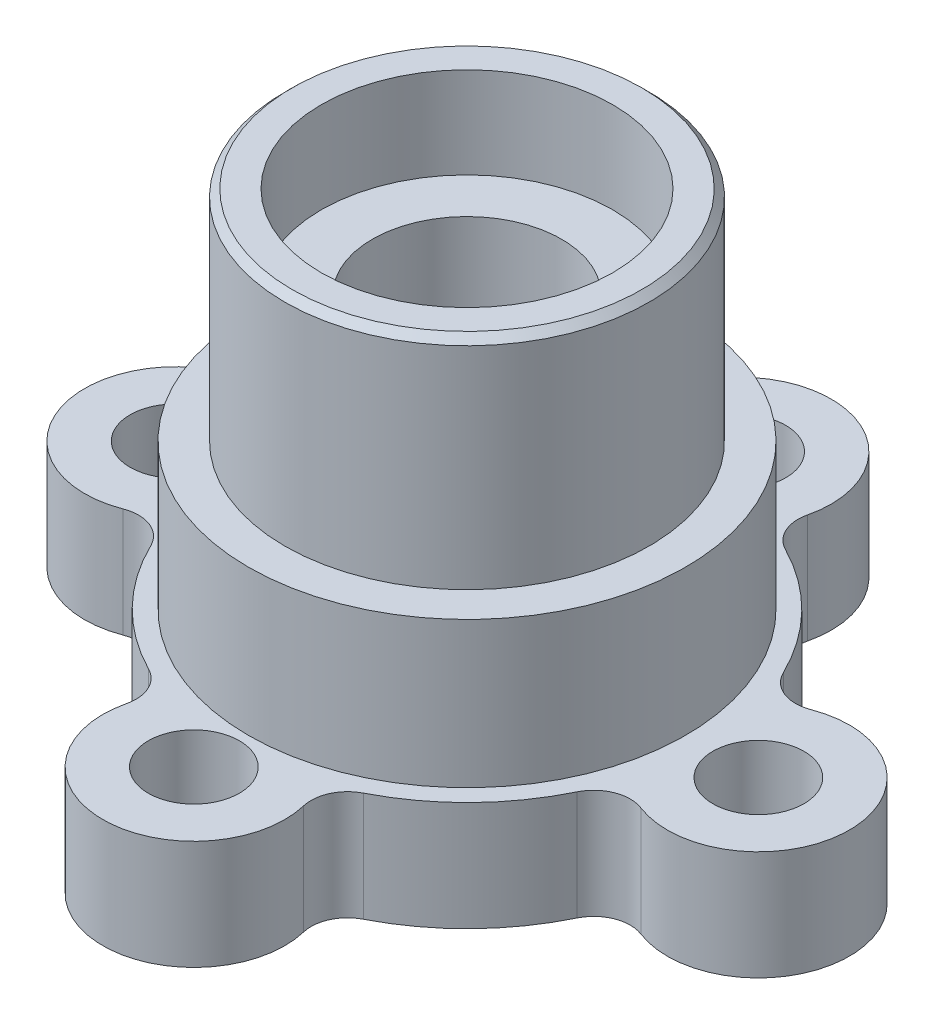
SolidWorks part; units mm, degrees
material "1060 Alloy"
ref_plane "Front Plane" through (0, 0, 0) normal (0, 0, 1) x (1, 0, 0)
ref_plane "Top Plane" through (0, 0, 0) normal (0, 1, 0) x (1, 0, 0)
ref_plane "Right Plane" through (0, 0, 0) normal (1, 0, 0) x (0, 0, -1)
sketch "Sketch1" plane through (0, 0, 0) normal (0, 1, 0) x (1, 0, 0)
  line L0 (0, 0) -> (0, 7.9047) construction
  line L1 (0, 0) -> (8, 0) construction
  arc A0 (-2.1042, 6.15) -> (-6.25, 1.7854) centre (0, 0) ccw
  arc A1 (2.1042, 6.15) -> (-2.1042, 6.15) centre (0, 7.5) ccw
  arc A2 (6.25, -1.7854) -> (6.25, 1.7854) centre (8, 0) ccw
  arc A3 (-2.1042, -6.15) -> (2.1042, -6.15) centre (0, -7.5) ccw
  arc A4 (-6.25, 1.7854) -> (-6.25, -1.7854) centre (-8, 0) ccw
  arc A5 (6.25, 1.7854) -> (2.1042, 6.15) centre (0, 0) ccw
  arc A6 (2.1042, -6.15) -> (6.25, -1.7854) centre (0, 0) ccw
  arc A7 (-6.25, -1.7854) -> (-2.1042, -6.15) centre (0, 0) ccw
  dimension "D1" = 16
  dimension "D2" = 15
  dimension "D3" = 13
  dimension "D4" = 5
extrude "Boss-Extrude1" add sketch "Sketch1" along normal blind 3
sketch "Sketch2" plane through (0, 3, 0) normal (0, 1, 0) x (1, 0, 0)
  circle A0 centre (0, 0) radius 6
  dimension "D1" = 12
extrude "Boss-Extrude2" add sketch "Sketch2" along normal blind 4
sketch "Sketch3" plane through (0, 7, 0) normal (0, 1, 0) x (1, 0, 0)
  circle A0 centre (0, 0) radius 5
  dimension "D1" = 10
extrude "Boss-Extrude3" add sketch "Sketch3" along normal blind 6
sketch "Sketch4" plane through (0, 13, 0) normal (0, 1, 0) x (1, 0, 0)
  circle A0 centre (0, 0) radius 2.6
  dimension "D1" = 5.2
extrude "Cut-Extrude1" cut sketch "Sketch4" against normal through all
sketch "Sketch5" plane through (0, 13, 0) normal (0, 1, 0) x (1, 0, 0)
  circle A0 centre (0, 0) radius 4
  dimension "D1" = 8
extrude "Cut-Extrude2" cut sketch "Sketch5" against normal blind 2.5
sketch "Sketch6" plane through (0, 0, 0) normal (0, -1, 0) x (1, 0, 0)
  circle A0 centre (0, 0) radius 4
  dimension "D1" = 8
extrude "Cut-Extrude3" cut sketch "Sketch6" against normal blind 3
hole_wizard "M3x0.5 Tapped Hole1" positions "Sketch7" profile "Sketch8" tap size "M3x0.5" standard "JIS" end condition through all
sketch "Sketch7" plane through (0, 3, 0) normal (0, 1, 0) x (1, 0, 0)
  point P0 (0, 7.5)
  point P2 (8, 0)
  point P5 (0, -7.5)
  point P7 (-8, 0)
  point P17 (0, 0)
  point P18 (0.1338, 7.2678)
  point P19 (0, 0)
  point P20 (0, 7.4758)
  point P21 (4.6603, -7.8537)
  point P22 (0, -7.5)
  point P24 (4.6335, 7.5)
  point P25 (0, 7.5)
sketch "Sketch8" plane through (0, 3, -7.5) normal (1, 0, 0) x (0, 0, 1)
  line L0 (0, 0) -> (0, 3)
  line L1 (0, 3) -> (1.25, 3)
  line L2 (1.25, 3) -> (1.25, 0)
  line L5 (1.25, 0) -> (0, 0)
  line L11 (0, -6.35) -> (0, 107.95) construction
  dimension "Thru Tap Drill Dia." = 2.5
  dimension "Thru Tap Drill Depth" = 3
cosmetic thread "Hole Thread1" parameters "D2"=3
cosmetic thread "Hole Thread2" parameters "D2"=3
cosmetic thread "Hole Thread3" parameters "D2"=3
cosmetic thread "Hole Thread4" parameters "D2"=3
chamfer "Chamfer1" distance 0.2 angle 45 1 edges at (0, 13, 5)
fillet "Fillet1" radius 1 8 edges at (-6.25, 1.5, 1.7854) (-2.1042, 1.5, 6.15) (-6.25, 1.5, -1.7854) (-2.1042, 1.5, -6.15) (2.1042, 1.5, -6.15) (6.25, 1.5, -1.7854) (6.25, 1.5, 1.7854) (2.1042, 1.5, 6.15)
